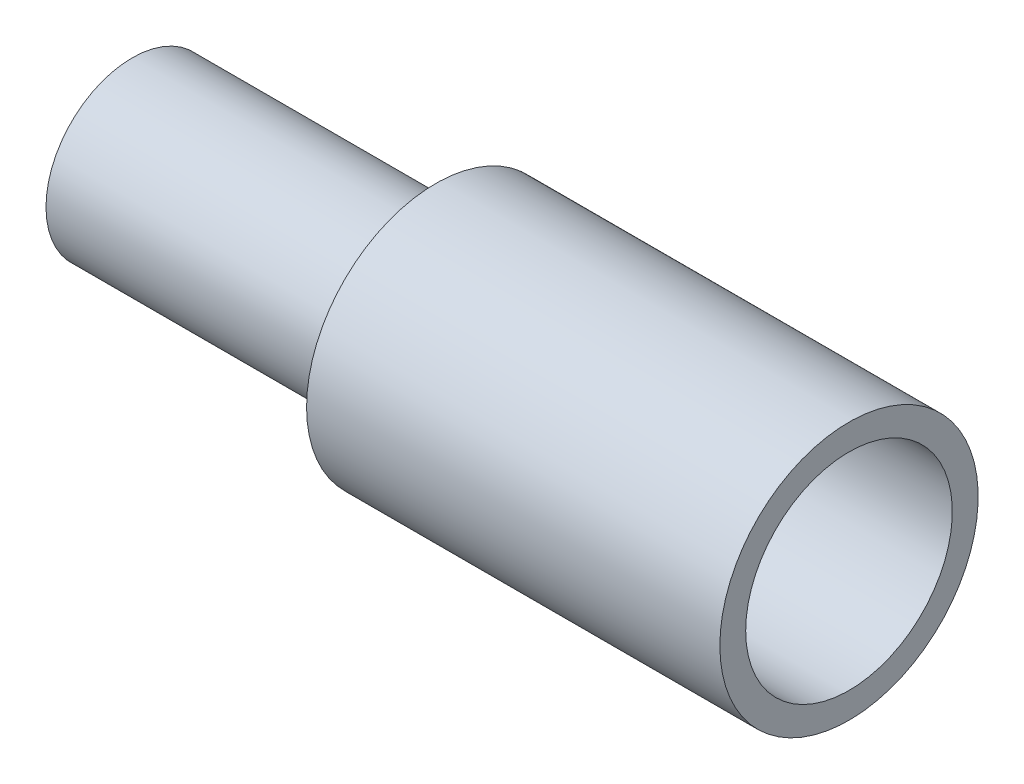
SolidWorks part; units mm, degrees
material "6061 Alloy"
ref_plane "Płaszczyzna przednia" through (0, 0, 0) normal (0, 0, 1) x (1, 0, 0)
ref_plane "Płaszczyzna górna" through (0, 0, 0) normal (0, 1, 0) x (1, 0, 0)
ref_plane "Płaszczyzna prawa" through (0, 0, 0) normal (1, 0, 0) x (0, 0, -1)
sketch "Szkic1" plane through (0, 0, 0) normal (0, 0, 1) x (1, 0, 0)
  line L0 (0, 0) -> (94.9515, 0)
  line L1 (91.7854, 0) -> (91.7854, 16)
  line L2 (91.7854, 16) -> (31.7854, 16)
  line L3 (31.7854, 9.35) -> (31.7854, 16)
  line L4 (31.7854, 0) -> (31.7854, 9.35)
  line L12 (31.7854, 16) -> (27.7854, 16)
  line L15 (31.7854, 16) -> (31.7854, 20)
  line L17 (12.7854, 0) -> (12.7854, 9.35)
  line L18 (27.7854, 16) -> (27.7854, 20)
  line L19 (27.7854, 20) -> (31.7854, 20)
  line L20 (31.7854, 20) -> (91.7854, 20)
  line L21 (91.7854, 20) -> (91.7854, 16)
  line L22 (27.7854, 16) -> (27.7854, 13.35)
  line L23 (12.7854, 13.35) -> (27.7854, 13.35)
  line L24 (12.7854, 9.35) -> (31.7854, 9.35)
  line L25 (12.7854, 13.35) -> (-19.2146, 13.35)
  line L26 (12.7854, 9.35) -> (12.7854, 13.35)
  line L27 (-19.2146, 13.35) -> (-19.2146, 0)
  line L28 (-19.2146, 0) -> (0, 0)
  line L29 (12.7854, 9.35) -> (-19.2146, 9.35)
revolve "Obrót1" add sketch "Szkic1" angle 360 about L28
